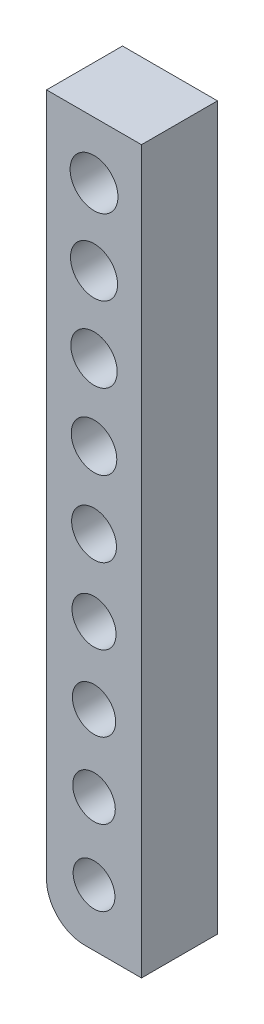
SolidWorks part; units mm, degrees
ref_plane "Front Plane" through (0, 0, 0) normal (1, 0, 0) x (0, 1, 0)
ref_plane "Top Plane" through (0, 0, 0) normal (0, 0, 1) x (0, 1, 0)
ref_plane "Right Plane" through (0, 0, 0) normal (0, 1, 0) x (-1, 0, 0)
sketch "Sketch1" plane through (0, 0, 0) normal (0, 0, 1) x (0, 1, 0)
  line L0 (0, 3.175) -> (48.26, 3.175) construction
  line L1 (0, 0) -> (48.26, 0)
  line L2 (0, 0) -> (0, 6.35)
  line L3 (0, 6.35) -> (48.26, 6.35)
  line L4 (48.26, 0) -> (48.26, 6.35)
  circle A0 centre (3.81, 3.175) radius 1.397
  circle A1 centre (8.89, 3.175) radius 1.4224
  circle A2 centre (13.97, 3.175) radius 1.4478
  circle A3 centre (19.05, 3.175) radius 1.4732
  circle A4 centre (24.13, 3.175) radius 1.4986
  circle A5 centre (29.21, 3.175) radius 1.524
  circle A6 centre (34.29, 3.175) radius 1.5494
  circle A7 centre (39.37, 3.175) radius 1.5748
  circle A8 centre (44.45, 3.175) radius 1.6002
  point P7 (3.81, 3.175)
  point P12 (8.89, 3.175)
  point P13 (13.97, 3.175)
  point P14 (19.05, 3.175)
  point P15 (24.13, 3.175)
  point P16 (29.21, 3.175)
  point P17 (34.29, 3.175)
  point P18 (39.37, 3.175)
  point P19 (44.45, 3.175)
  dimension "D3" = 2.794
  dimension "D2" = 3.81
  dimension "D6" = 2.8448
  dimension "D7" = 2.8956
  dimension "D8" = 2.9464
  dimension "D9" = 2.9972
  dimension "D10" = 3.048
  dimension "D11" = 3.0988
  dimension "D12" = 3.1496
  dimension "D13" = 3.2004
  dimension "D1" = 6.35
  dimension "D5" = 5.08
  dimension "D14" = 3.81
  dimension "D4" = 9
extrude "Boss-Extrude1" add sketch "Sketch1" along normal blind 5.08
fillet "Fillet1" radius 2.54 1 edges at (-6.35, 0, 2.54)
